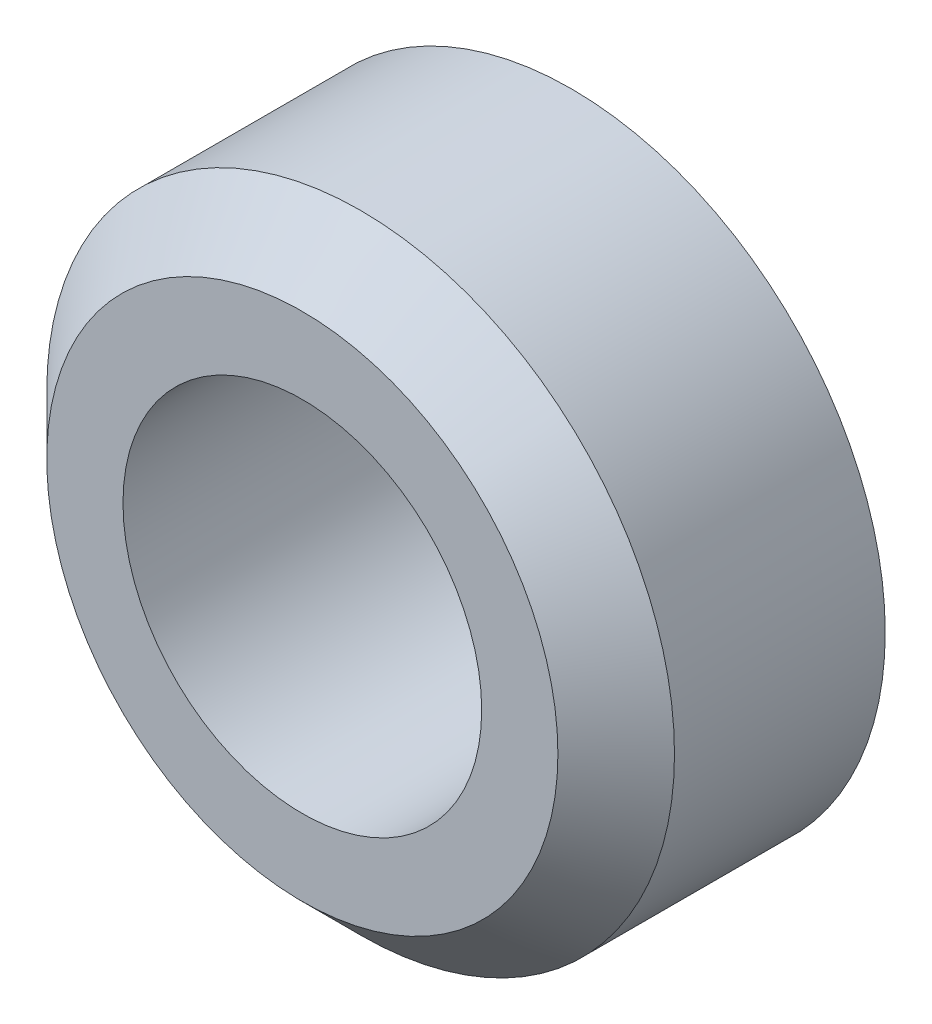
SolidWorks part; units mm, degrees
ref_plane "Front Plane" through (0, 0, 0) normal (1, 0, 0) x (0, 1, 0)
ref_plane "Top Plane" through (0, 0, 0) normal (0, 0, 1) x (0, 1, 0)
ref_plane "Right Plane" through (0, 0, 0) normal (0, 1, 0) x (-1, 0, 0)
sketch "Sketch2" plane through (0, 0, 0) normal (0, 0, 1) x (0, 1, 0)
  circle A0 centre (0, 0) radius 4
  circle A1 centre (0, 0) radius 7
  dimension "D1" = 8
  dimension "D2" = 14
extrude "Boss-Extrude1" add sketch "Sketch2" along normal blind 6
chamfer "Chamfer1" distance 1.3 angle 45 1 edges at (7, 0, 6)
